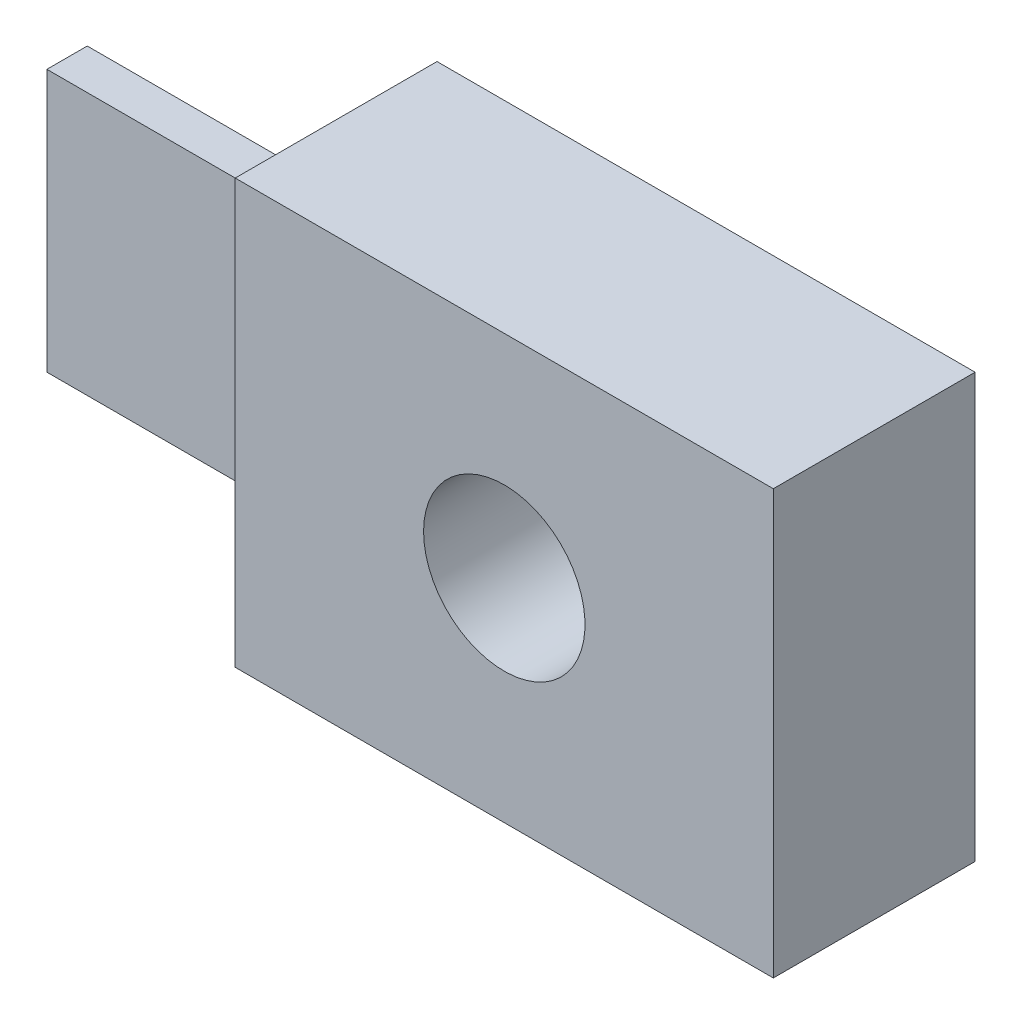
SolidWorks part; units mm, degrees
material "1023 Carbon Steel Sheet (SS)"
ref_plane "Front Plane" through (0, 0, 0) normal (0, 0, 1) x (1, 0, 0)
ref_plane "Top Plane" through (0, 0, 0) normal (0, 1, 0) x (1, 0, 0)
ref_plane "Right Plane" through (0, 0, 0) normal (1, 0, 0) x (0, 0, -1)
sketch "Sketch1" plane through (0, 0, 0) normal (0, 0, 1) x (1, 0, 0)
  line L1 (-20, -15.75) -> (20, -15.75)
  line L2 (-20, -15.75) -> (-20, 15.75)
  line L3 (-20, 15.75) -> (20, 15.75)
  line L4 (20, -15.75) -> (20, 15.75)
  line L5 (-20, -15.75) -> (20, 15.75) construction
  line L6 (-20, 15.75) -> (20, -15.75) construction
  point P0 (0, 0)
  dimension "D1" = 31.5
  dimension "D2" = 40
extrude "Boss-Extrude1" add sketch "Sketch1" along normal blind 15
sketch "Sketch2" plane through (-20, 0, 0) normal (-1, 0, 0) x (0, 0, 1)
  line L0 (0, 15.75) -> (15, -15.75) construction
  line L1 (0, -15.75) -> (15, 15.75) construction
  line L2 (0, 15.75) -> (0, -15.75) construction
  line L3 (6, -9.75) -> (9, -9.75)
  line L4 (6, -9.75) -> (6, 9.75)
  line L5 (6, 9.75) -> (9, 9.75)
  line L6 (9, -9.75) -> (9, 9.75)
  line L7 (6, -9.75) -> (9, 9.75) construction
  line L8 (6, 9.75) -> (9, -9.75) construction
  line L9 (15, 15.75) -> (0, 15.75) construction
  point P8 (7.5, 0)
  dimension "D1" = 6
  dimension "D2" = 6
extrude "Boss-Extrude2" add sketch "Sketch2" along normal blind 20
sketch "Sketch3" plane through (0, 0, 0) normal (0, 0, -1) x (-1, 0, 0)
  circle A0 centre (0, 0) radius 6
  dimension "D1" = 12
extrude "Cut-Extrude1" cut sketch "Sketch3" against normal through all
equation "\"StrutHeight\"=31.5"
equation "\"D1@Sketch1\"=\"StrutHeight\""
equation "\"StrutWidth\"= 15"
equation "\"D1@Boss-Extrude1\"=\"StrutWidth\""
equation "\"StrutWallThickness\"=6"
equation "\"D1@Sketch2\"=\"StrutWallThickness\""
equation "\"D2@Sketch2\"=\"StrutWallThickness\""
